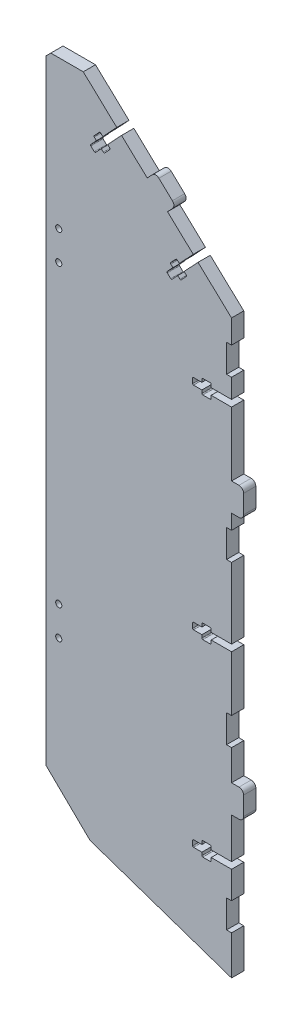
SolidWorks part; units mm, degrees
ref_plane "Front Plane" through (0, 0, 0) normal (0, 0, 1) x (1, 0, 0)
ref_plane "Top Plane" through (0, 0, 0) normal (0, 1, 0) x (1, 0, 0)
ref_plane "Right Plane" through (0, 0, 0) normal (1, 0, 0) x (0, 0, -1)
sketch "Model" plane through (0, 0, 0) normal (0, 0, 1) x (1, 0, 0)
  line L0 (-2.7, 21.1) -> (0, 21.1)
  line L1 (0, 0) -> (0, 21.1)
  line L2 (-76.35, 26.1117) -> (0, 0)
  line L3 (-100, 380.9) -> (-100, 49.2)
  line L4 (-97.5, 383.4) -> (-100, 380.9)
  line L5 (-80, 383.4) -> (-97.5, 383.4)
  line L6 (-61.9203, 366.4503) -> (-80, 383.4)
  line L7 (-69.4437, 358.4254) -> (-61.9203, 366.4503)
  line L8 (-70.6, 359.5094) -> (-69.4437, 358.4254)
  line L9 (-74.0425, 356.5685) -> (-71.3067, 359.4866)
  line L10 (-72.8634, 354.7777) -> (-74.0197, 355.8617)
  line L11 (-75.9411, 351.4948) -> (-72.8634, 354.7777)
  line L12 (-74.058, 349.044) -> (-75.9183, 350.788)
  line L13 (-70.2735, 352.3497) -> (-73.3512, 349.0668)
  line L14 (-69.1172, 351.2657) -> (-70.2735, 352.3497)
  line L15 (-65.6747, 354.2066) -> (-68.4105, 351.2885)
  line L16 (-66.8538, 355.9974) -> (-65.6975, 354.9133)
  line L17 (-59.3305, 364.0223) -> (-66.8538, 355.9974)
  line L18 (-45.4692, 351.0274) -> (-59.3305, 364.0223)
  line L19 (-45.4692, 351.0274) -> (-42.7335, 353.9456)
  line L20 (-39.1998, 354.0596) -> (-31.9044, 347.2201)
  line L21 (-31.7904, 343.6865) -> (-34.5262, 340.7683)
  line L22 (-20.665, 327.7734) -> (-34.5262, 340.7683)
  line L23 (-28.1883, 319.7485) -> (-20.665, 327.7734)
  line L24 (-29.3447, 320.8326) -> (-28.1883, 319.7485)
  line L25 (-32.7872, 317.8916) -> (-30.0514, 320.8098)
  line L26 (-31.608, 316.1008) -> (-32.7644, 317.1849)
  line L27 (-34.6858, 312.8179) -> (-31.608, 316.1008)
  line L28 (-32.8027, 310.3671) -> (-34.663, 312.1112)
  line L29 (-29.0182, 313.6728) -> (-32.0959, 310.3899)
  line L30 (-27.8619, 312.5888) -> (-29.0182, 313.6728)
  line L31 (-24.4194, 315.5297) -> (-27.1551, 312.6116)
  line L32 (-25.5985, 317.3205) -> (-24.4422, 316.2365)
  line L33 (-18.0751, 325.3454) -> (-25.5985, 317.3205)
  line L34 (0, 308.4) -> (-18.0751, 325.3454)
  line L35 (0, 295.7) -> (0, 308.4)
  line L36 (0, 295.7) -> (-2.7, 295.7)
  line L37 (-2.7, 295.7) -> (-2.7, 280.7)
  line L38 (-2.7, 280.7) -> (0, 280.7)
  line L39 (0, 270.3) -> (0, 280.7)
  line L40 (-11, 270.3) -> (0, 270.3)
  line L41 (-11, 271.885) -> (-11, 270.3)
  line L42 (-15.5, 272.385) -> (-11.5, 272.385)
  line L43 (-16, 270.3) -> (-16, 271.885)
  line L44 (-20.5, 270.3) -> (-16, 270.3)
  line L45 (-21, 267.25) -> (-21, 269.8)
  line L46 (-16, 266.75) -> (-20.5, 266.75)
  line L47 (-16, 265.165) -> (-16, 266.75)
  line L48 (-11.5, 264.665) -> (-15.5, 264.665)
  line L49 (-11, 266.75) -> (-11, 265.165)
  line L50 (0, 266.75) -> (-11, 266.75)
  line L51 (0, 232.2) -> (0, 266.75)
  line L52 (4, 232.2) -> (0, 232.2)
  line L53 (6.5, 219.7) -> (6.5, 229.7)
  line L54 (4, 217.2) -> (0, 217.2)
  line L55 (0, 209.1667) -> (0, 217.2)
  line L56 (0, 209.1667) -> (-2.7, 209.1667)
  line L57 (-2.7, 209.1667) -> (-2.7, 194.1667)
  line L58 (-2.7, 194.1667) -> (0, 194.1667)
  line L59 (0, 155.975) -> (0, 194.1667)
  line L60 (-11, 155.975) -> (0, 155.975)
  line L61 (-11, 157.56) -> (-11, 155.975)
  line L62 (-15.5, 158.06) -> (-11.5, 158.06)
  line L63 (-16, 155.975) -> (-16, 157.56)
  line L64 (-20.5, 155.975) -> (-16, 155.975)
  line L65 (-21, 152.925) -> (-21, 155.475)
  line L66 (-16, 152.425) -> (-20.5, 152.425)
  line L67 (-16, 150.84) -> (-16, 152.425)
  line L68 (-11.5, 150.34) -> (-15.5, 150.34)
  line L69 (-11, 152.425) -> (-11, 150.84)
  line L70 (0, 152.425) -> (-11, 152.425)
  line L71 (0, 122.6333) -> (0, 152.425)
  line L72 (0, 122.6333) -> (-2.7, 122.6333)
  line L73 (-2.7, 122.6333) -> (-2.7, 107.6333)
  line L74 (-2.7, 107.6333) -> (0, 107.6333)
  line L75 (0, 91.2) -> (0, 107.6333)
  line L76 (4, 91.2) -> (0, 91.2)
  line L77 (6.5, 78.7) -> (6.5, 88.7)
  line L78 (4, 76.2) -> (0, 76.2)
  line L79 (0, 54.35) -> (0, 76.2)
  line L80 (-11, 54.35) -> (0, 54.35)
  line L81 (-11, 55.935) -> (-11, 54.35)
  line L82 (-15.5, 56.435) -> (-11.5, 56.435)
  line L83 (-16, 54.35) -> (-16, 55.935)
  line L84 (-20.5, 54.35) -> (-16, 54.35)
  line L85 (-21, 51.3) -> (-21, 53.85)
  line L86 (-16, 50.8) -> (-20.5, 50.8)
  line L87 (-16, 49.215) -> (-16, 50.8)
  line L88 (-11.5, 48.715) -> (-15.5, 48.715)
  line L89 (-11, 50.8) -> (-11, 49.215)
  line L90 (0, 50.8) -> (-11, 50.8)
  line L91 (0, 36.1) -> (0, 50.8)
  line L92 (0, 36.1) -> (-2.7, 36.1)
  line L93 (-2.7, 36.1) -> (-2.7, 21.1)
  line L94 (-100, 49.2) -> (-76.35, 26.1117)
  circle A0 centre (-93.2096, 128.1223) radius 1.6637
  circle A1 centre (-93.2096, 112.2473) radius 1.6637
  circle A2 centre (-93.2096, 303.5223) radius 1.6637
  circle A3 centre (-93.2096, 287.6473) radius 1.6637
  arc A4 (-70.6, 359.5094) -> (-71.3067, 359.4866) centre (-70.942, 359.1447) ccw
  arc A5 (-74.0425, 356.5685) -> (-74.0197, 355.8617) centre (-73.6777, 356.2265) ccw
  arc A6 (-75.9411, 351.4948) -> (-75.9183, 350.788) centre (-75.5763, 351.1528) ccw
  arc A7 (-74.058, 349.044) -> (-73.3512, 349.0668) centre (-73.716, 349.4088) ccw
  arc A8 (-69.1172, 351.2657) -> (-68.4105, 351.2885) centre (-68.7752, 351.6304) ccw
  arc A9 (-65.6747, 354.2066) -> (-65.6975, 354.9133) centre (-66.0395, 354.5486) ccw
  arc A10 (-39.1998, 354.0596) -> (-42.7335, 353.9456) centre (-40.9096, 352.2357) ccw
  arc A11 (-31.7904, 343.6865) -> (-31.9044, 347.2201) centre (-33.6143, 345.3963) ccw
  arc A12 (-29.3447, 320.8326) -> (-30.0514, 320.8098) centre (-29.6866, 320.4678) ccw
  arc A13 (-32.7872, 317.8916) -> (-32.7644, 317.1849) centre (-32.4224, 317.5496) ccw
  arc A14 (-34.6858, 312.8179) -> (-34.663, 312.1112) centre (-34.321, 312.4759) ccw
  arc A15 (-32.8027, 310.3671) -> (-32.0959, 310.3899) centre (-32.4607, 310.7319) ccw
  arc A16 (-27.8619, 312.5888) -> (-27.1551, 312.6116) centre (-27.5199, 312.9536) ccw
  arc A17 (-24.4194, 315.5297) -> (-24.4422, 316.2365) centre (-24.7841, 315.8717) ccw
  arc A18 (-11, 271.885) -> (-11.5, 272.385) centre (-11.5, 271.885) ccw
  arc A19 (-15.5, 272.385) -> (-16, 271.885) centre (-15.5, 271.885) ccw
  arc A20 (-20.5, 270.3) -> (-21, 269.8) centre (-20.5, 269.8) ccw
  arc A21 (-21, 267.25) -> (-20.5, 266.75) centre (-20.5, 267.25) ccw
  arc A22 (-16, 265.165) -> (-15.5, 264.665) centre (-15.5, 265.165) ccw
  arc A23 (-11.5, 264.665) -> (-11, 265.165) centre (-11.5, 265.165) ccw
  arc A24 (6.5, 229.7) -> (4, 232.2) centre (4, 229.7) ccw
  arc A25 (4, 217.2) -> (6.5, 219.7) centre (4, 219.7) ccw
  arc A26 (-11, 157.56) -> (-11.5, 158.06) centre (-11.5, 157.56) ccw
  arc A27 (-15.5, 158.06) -> (-16, 157.56) centre (-15.5, 157.56) ccw
  arc A28 (-20.5, 155.975) -> (-21, 155.475) centre (-20.5, 155.475) ccw
  arc A29 (-21, 152.925) -> (-20.5, 152.425) centre (-20.5, 152.925) ccw
  arc A30 (-16, 150.84) -> (-15.5, 150.34) centre (-15.5, 150.84) ccw
  arc A31 (-11.5, 150.34) -> (-11, 150.84) centre (-11.5, 150.84) ccw
  arc A32 (6.5, 88.7) -> (4, 91.2) centre (4, 88.7) ccw
  arc A33 (4, 76.2) -> (6.5, 78.7) centre (4, 78.7) ccw
  arc A34 (-11, 55.935) -> (-11.5, 56.435) centre (-11.5, 55.935) ccw
  arc A35 (-15.5, 56.435) -> (-16, 55.935) centre (-15.5, 55.935) ccw
  arc A36 (-20.5, 54.35) -> (-21, 53.85) centre (-20.5, 53.85) ccw
  arc A37 (-21, 51.3) -> (-20.5, 50.8) centre (-20.5, 51.3) ccw
  arc A38 (-16, 49.215) -> (-15.5, 48.715) centre (-15.5, 49.215) ccw
  arc A39 (-11.5, 48.715) -> (-11, 49.215) centre (-11.5, 49.215) ccw
extrude "Boss-Extrude1" add sketch "Model" along normal blind 6.6
